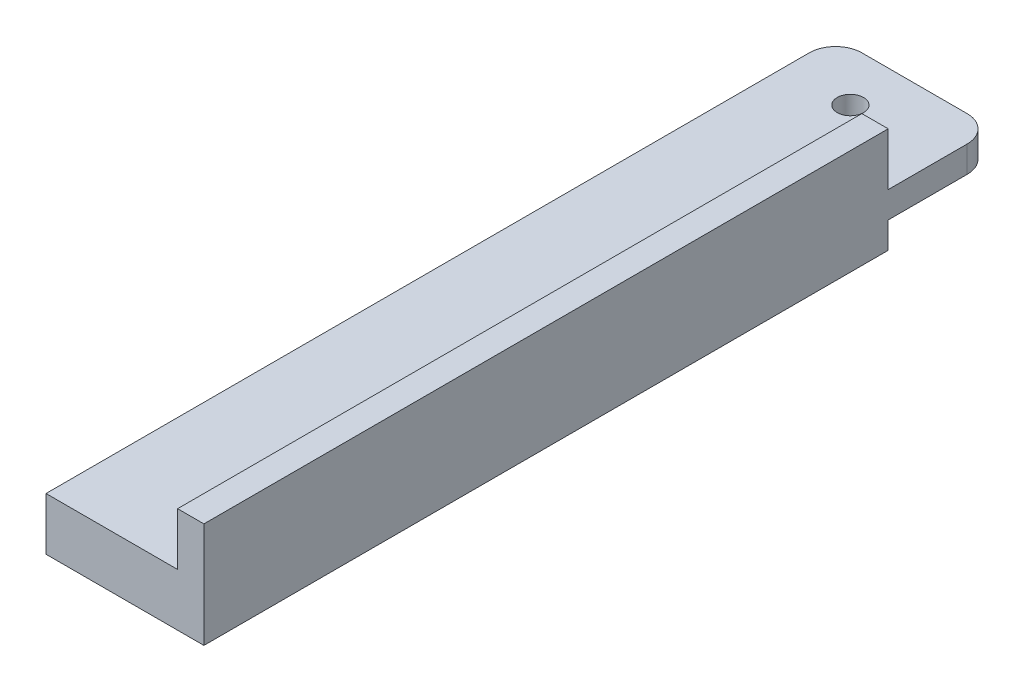
SolidWorks part; units mm, degrees
material "3.0205 (EN-AW 1200)"
ref_plane "前视基准面" through (0, 0, 0) normal (0, 0, 1) x (1, 0, 0)
ref_plane "上视基准面" through (0, 0, 0) normal (0, 1, 0) x (1, 0, 0)
ref_plane "右视基准面" through (0, 0, 0) normal (1, 0, 0) x (0, 0, -1)
other "Configuration Table"
sketch "草图1" plane through (0, 0, 0) normal (0, 0, 1) x (1, 0, 0)
  line L0 (0, 0) -> (0, -40)
  line L1 (0, -40) -> (60, -40)
  line L5 (10, 0) -> (0, 0)
  line L10 (60, -40) -> (60, -20)
  line L11 (60, -20) -> (10, -20)
  line L12 (10, -20) -> (10, 0)
  dimension "D4" = 40
extrude "凸台-拉伸1" add sketch "草图1" along normal blind 300
sketch "草图2" plane through (0, 0, 0) normal (0, 0, -1) x (-1, 0, 0)
  line L7 (-10, -20) -> (0, -20)
  line L8 (0, 0) -> (0, -40) construction
  line L9 (0, -20) -> (0, 0)
  line L10 (0, 0) -> (-10, 0)
  line L12 (-10, -30) -> (0, -30)
  line L13 (0, -30) -> (0, -40)
  line L14 (0, -40) -> (-10, -40)
  line L19 (-10, -30) -> (-60, -30)
  line L20 (-60, -30) -> (-60, -40)
  line L21 (-60, -40) -> (-10, -40)
  line L22 (-10, 0) -> (-10, -20)
extrude "切除-拉伸1" cut sketch "草图2" against normal blind 40
sketch "草图4" plane through (0, -20, 0) normal (0, 1, 0) x (1, 0, 0)
  circle A2 centre (35, -19.3649) radius 5
extrude "切除-拉伸2" cut sketch "草图4" against normal through all both
mirror "镜向1" about plane through (0, 0, 300) normal (1, 0, 0) of "切除-拉伸2", "切除-拉伸1", "凸台-拉伸1"
sketch "草图6" plane through (0, 0, 0) normal (0, 1, 0) x (1, 0, 0)
  line L2 (0, -314.937) -> (157.4398, -317.8525)
  line L3 (157.4398, -317.8525) -> (163.765, 23.7053)
  line L4 (163.765, 23.7053) -> (0, 26.738)
  line L5 (0, 26.738) -> (0, -314.937)
extrude "切除-拉伸3" cut sketch "草图6" against normal through all
fillet "圆角1" radius 10 2 edges at (-60, -25, 0) (0, -25, 0)
